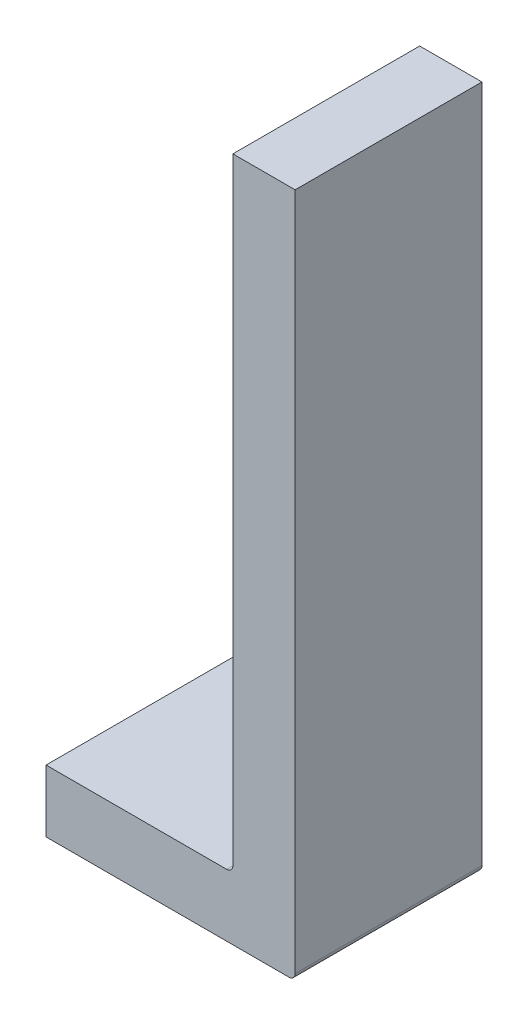
SolidWorks part; units mm, degrees
ref_plane "Front Plane" through (0, 0, 0) normal (0, 0, 1) x (1, 0, 0)
ref_plane "Top Plane" through (0, 0, 0) normal (0, 1, 0) x (1, 0, 0)
ref_plane "Right Plane" through (0, 0, 0) normal (1, 0, 0) x (0, 0, -1)
sketch "Sketch2" plane through (0, 0, 0) normal (0, 1, 0) x (1, 0, 0)
  line L1 (0, 0) -> (20, 0)
  line L2 (0, 0) -> (0, 15)
  line L3 (0, 15) -> (20, 15)
  line L4 (20, 0) -> (20, 15)
extrude "Boss-Extrude1" add sketch "Sketch2" along normal blind 5
sketch "Sketch3" plane through (0, 5, 0) normal (0, 1, 0) x (1, 0, 0)
  line L0 (0, 0) -> (15, 0)
  line L1 (0, 0) -> (20, 0) construction
  line L2 (15, 0) -> (15, 15)
  line L3 (20, 15) -> (0, 15) construction
  line L4 (15, 0) -> (20, 0)
  line L5 (20, 0) -> (20, 15)
  line L6 (20, 15) -> (15, 15)
  line M2 (0, 0) -> (20, 0)
  line M3 (20, 0) -> (20, 15)
  line M4 (20, 15) -> (0, 15)
extrude "Boss-Extrude2" add sketch "Sketch3" along normal blind 50 contours L2 M2 M3 M4
fillet "Fillet1" radius 0.5 1 edges at (20, 0, -7.5)
fillet "Fillet2" radius 0.5 1 edges at (15, 5, -7.5)
